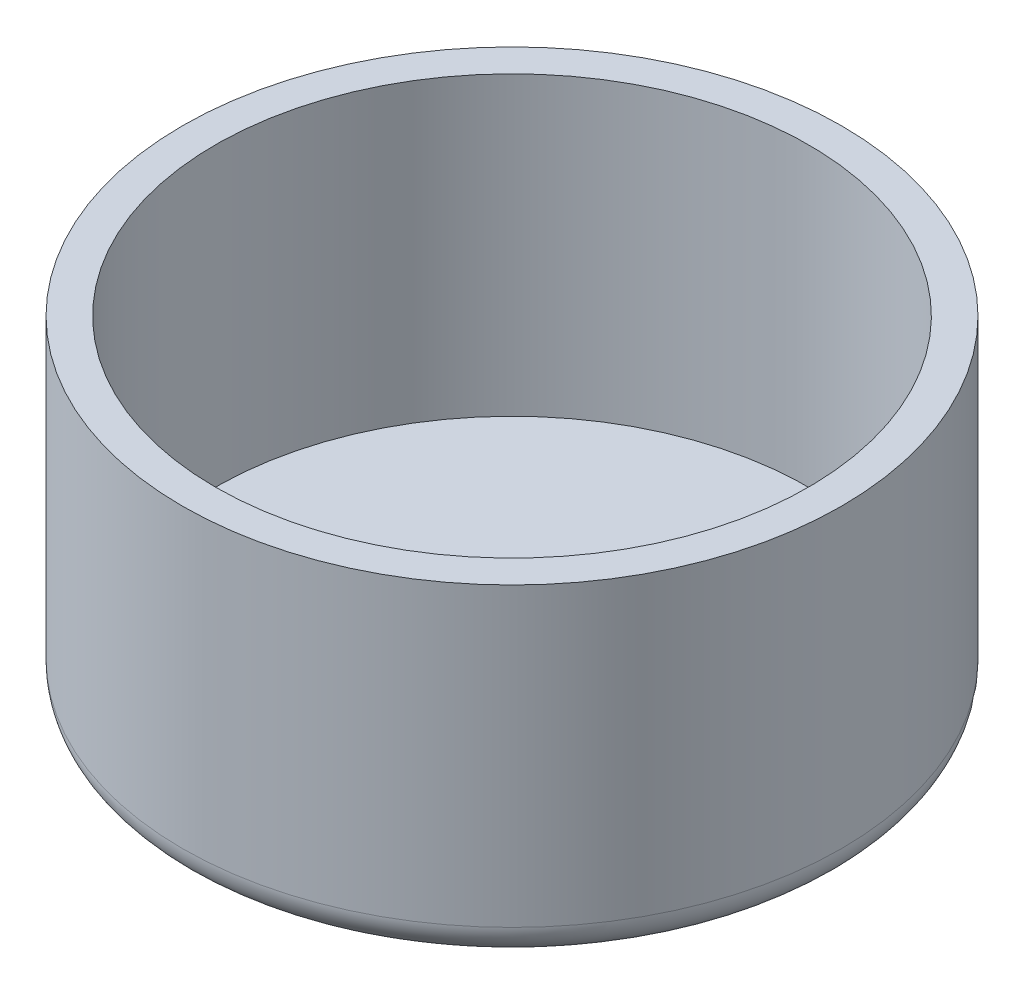
SolidWorks part; units mm, degrees
ref_plane "Front Plane" through (0, 0, 0) normal (0, 0, 1) x (1, 0, 0)
ref_plane "Top Plane" through (0, 0, 0) normal (0, 1, 0) x (1, 0, 0)
ref_plane "Right Plane" through (0, 0, 0) normal (1, 0, 0) x (0, 0, -1)
sketch "Sketch1" plane through (0, 0, 0) normal (0, 1, 0) x (1, 0, 0)
  circle A0 centre (0, 0) radius 100
extrude "Boss-Extrude1" add sketch "Sketch1" along normal blind 100
sketch "Sketch2" plane through (0, 100, 0) normal (0, 1, 0) x (1, 0, 0)
  circle A0 centre (0, 0) radius 90
extrude "Cut-Extrude1" cut sketch "Sketch2" against normal blind 90
fillet "Fillet1" radius 10 1 edges at (0, 0, 100)
sketch "Sketch3" plane through (0, 0, 0) normal (0, -1, 0) x (1, 0, 0)
  circle A1 centre (0, 0) radius 5
extrude "Boss-Extrude2" add sketch "Sketch3" along normal blind 5
sketch "Sketch4" plane through (0, -5, 0) normal (0, -1, 0) x (-1, 0, 0)
  circle A0 centre (0, 0) radius 3
extrude "Cut-Extrude2" cut sketch "Sketch4" against normal blind 5
